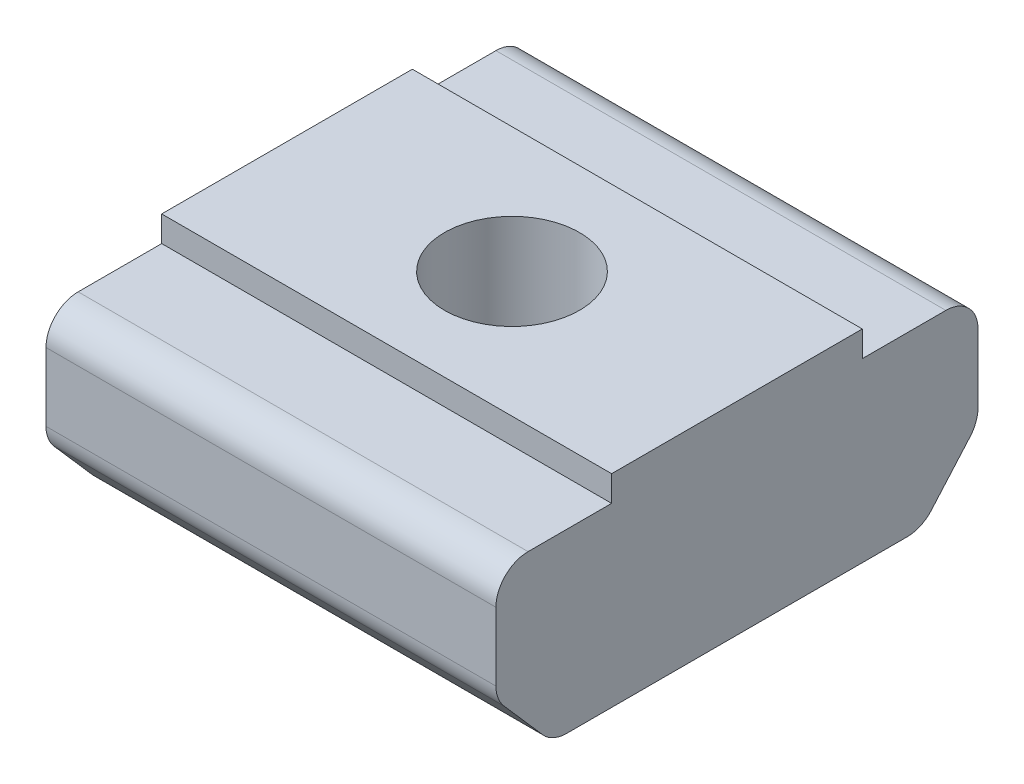
SolidWorks part; units mm, degrees
ref_plane "Front Plane" through (0, 0, 0) normal (0, 0, 1) x (1, 0, 0)
ref_plane "Top Plane" through (0, 0, 0) normal (0, 1, 0) x (1, 0, 0)
ref_plane "Right Plane" through (0, 0, 0) normal (1, 0, 0) x (0, 0, -1)
ref_plane "Plane1" through (-7, 0, 0) normal (1, 0, 0) x (0, 0, -1)
ref_plane "Plane2" through (-4.2, 0, 0) normal (1, 0, 0) x (0, 0, -1)
sketch "Axis_Line_X" plane through (0, 0, 0) normal (0, 1, 0) x (1, 0, 0)
  line L0 (0, 0) -> (50, 0)
  dimension "FIX_3" = 50
sketch "Axis_Line_Z" plane through (0, 0, 0) normal (0, 1, 0) x (1, 0, 0)
  line L0 (0, 0) -> (0, -50)
  dimension "FIX_4" = 50
sketch "Sketch1" plane through (-7, 0, 0) normal (1, 0, 0) x (0, 0, -1)
  line L0 (5.75, -6.3) -> (-5.75, -6.3)
  line L1 (-7.5, -0.8) -> (-7.5, -4.3)
  line L2 (-7.5, -0.8) -> (-3.9, -0.8)
  line L3 (-3.9, -0.8) -> (-3.9, 0)
  line L4 (-3.9, 0) -> (3.9, 0)
  line L5 (3.9, 0) -> (3.9, -0.8)
  line L6 (3.9, -0.8) -> (7.5, -0.8)
  line L7 (7.5, -0.8) -> (7.5, -4.3)
  line L8 (7.5, -4.3) -> (5.75, -6.3)
  line L9 (0, 0) -> (0, -6.3) construction
  line L10 (-7.5, -4.3) -> (-5.75, -6.3)
  point P15 (-7.5, -0.8)
  point P18 (-7.5, -4.3)
  point P21 (-5.75, -6.3)
  point P24 (5.75, -6.3)
  point P27 (7.5, -4.3)
  point P30 (7.5, -0.8)
  dimension "FIX_8" = 5.5
  dimension "FIX_6" = 7.8
  dimension "FIX_7" = 6.3
  dimension "FIX_9" = 3.5
  dimension "FIX_5" = 15
  dimension "FIX_10" = 11.5
extrude "Boss-Extrude1" add sketch "Sketch1" along normal blind 14
fillet "Fillet1" radius 1 6 edges at (0, -0.8, 7.5) (0, -4.3, 7.5) (0, -6.3, 5.75) (0, -6.3, -5.75) (0, -4.3, -7.5) (0, -0.8, -7.5)
hole_wizard "Tapped Hole1" positions "Sketch3" profile "Sketch2" tap size "M5x0.8" standard "JIS" end condition through all
sketch "Sketch3" plane through (0, 0, 0) normal (0, 1, 0) x (1, 0, 0)
  point P0 (0, 0)
cosmetic thread "Thread1" parameters "NFIX_1"=5
sketch "Sketch2" plane through (0, 0, 0) normal (1, 0, 0) x (0, 0, 1)
  line L0 (0, 0) -> (0, 6.3)
  line L1 (0, 6.3) -> (2.1, 6.3)
  line L2 (2.1, 6.3) -> (2.1, 0)
  line L5 (2.1, 0) -> (0, 0)
  line L11 (0, 0) -> (0, 6.3) construction
  dimension "Thru Tap Drill Dia." = 4.2
  dimension "Thru Tap Drill Depth" = 6.3
sketch "Sketch4" [suppressed] plane through (-4.2, 0, 0) normal (1, 0, 0) x (0, 0, -1)
  line L0 (6.1, -0.75) -> (6.1, -0.8)
  line L1 (6.1, -0.8) -> (6.15, -0.8)
  line L2 (6.1, -0.75) -> (6.1, -0.8) construction
  arc A0 (6.15, -0.8) -> (6.1, -0.75) centre (6.1, -0.8) ccw
  dimension "FIX_14" = 0.1
  dimension "FIX_13" = 0.8
  dimension "FIX_12" = 6.1
revolve "Revolve1" [suppressed] add sketch "Sketch4" angle 360 about L2
pattern_linear "LPattern1" [suppressed]
